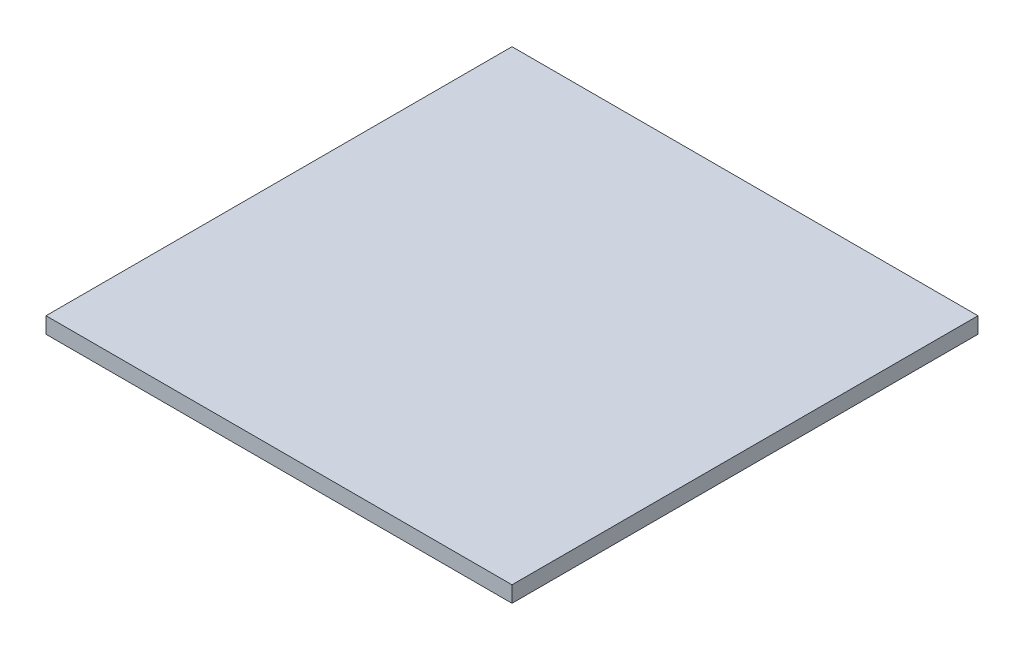
SolidWorks part; units mm, degrees
ref_plane "Front Plane" through (0, 0, 0) normal (0, 0, 1) x (1, 0, 0)
ref_plane "Top Plane" through (0, 0, 0) normal (0, 1, 0) x (1, 0, 0)
ref_plane "Right Plane" through (0, 0, 0) normal (1, 0, 0) x (0, 0, -1)
ref_plane "Plane1" through (0, 23, 0) normal (0, 1, 0) x (1, 0, 0)
sketch "Sketch1" plane through (0, 23, 0) normal (0, 1, 0) x (1, 0, 0)
  line L1 (184.4165, 43.4986) -> (97.4194, 43.4986)
  line L2 (184.4165, 43.4986) -> (184.4165, -43.4986)
  line L3 (184.4165, -43.4986) -> (97.4194, -43.4986)
  line L4 (97.4194, 43.4986) -> (97.4194, -43.4986)
  point P4 (97.4194, 0)
extrude "Boss-Extrude1" add sketch "Sketch1" along normal blind 3
